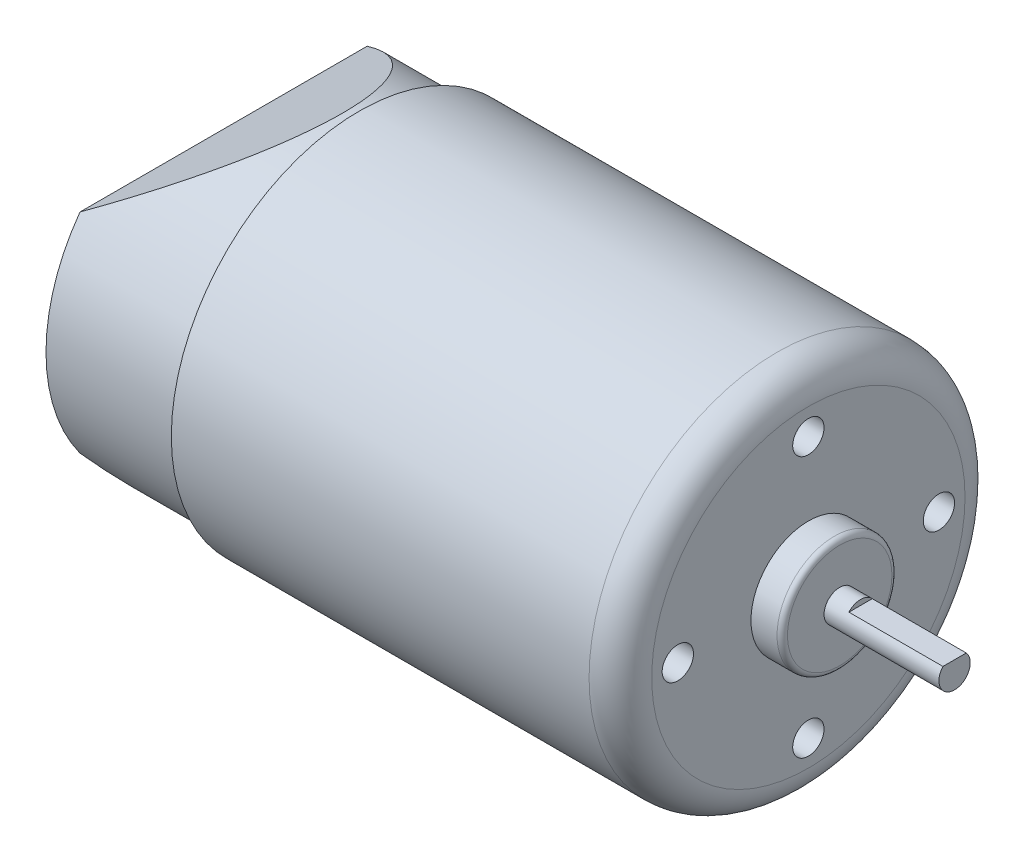
SolidWorks part; units mm, degrees
ref_plane "Front Plane" through (0, 0, 0) normal (0, 0, 1) x (1, 0, 0)
ref_plane "Top Plane" through (0, 0, 0) normal (0, 1, 0) x (1, 0, 0)
ref_plane "Right Plane" through (0, 0, 0) normal (1, 0, 0) x (0, 0, -1)
sketch "Sketch1" plane through (0, 0, 0) normal (1, 0, 0) x (0, 0, -1)
  circle A0 centre (0, 0) radius 18
  dimension "D1" = 36
extrude "Boss-Extrude1" add sketch "Sketch1" along normal blind 56
fillet "Fillet1" radius 3 1 edges at (56, 0, -18)
sketch "Sketch2" plane through (0, 0, 0) normal (0, 0, 1) x (1, 0, 0)
  line L0 (13, 18) -> (0, 10)
  line L1 (53, 18) -> (0, 18) construction
  line L2 (0, 18) -> (0, -18) construction
  line L3 (0, 10) -> (0, -10)
  line L4 (0, -10) -> (13, -18)
  line L5 (0, -18) -> (53, -18) construction
  line L6 (13, -18) -> (0, -18)
  line L7 (0, -18) -> (-7.8038, 17.2258)
  line L8 (-7.8038, 17.2258) -> (0, 18)
  line L9 (0, 18) -> (13, 18)
  dimension "D1" = 13
  dimension "D2" = 8
extrude "Cut-Extrude1" cut sketch "Sketch2" against normal up to surface and the other way up to surface
sketch "Sketch3" plane through (0, 0, 0) normal (0, 0, 1) x (1, 0, 0)
  line L0 (13, 18) -> (13, 17)
  line L1 (13, 17) -> (0, 17)
  line L2 (0, 17) -> (0, 18)
  line L3 (-7.8038, 17.2258) -> (0, 18) construction
  line L4 (0, 18) -> (13, 18)
  line L6 (0, 10) -> (0, -10) construction
  line L7 (-1000, 0) -> (49000, 0) construction
  dimension "D1" = 1
revolve "Cut-Revolve1" cut sketch "Sketch3" angle 360 about L7
sketch "Sketch4" plane through (56, 0, 0) normal (1, 0, 0) x (0, 0, -1)
  circle A0 centre (0, 0) radius 5.5
  dimension "D1" = 11
extrude "Boss-Extrude2" add sketch "Sketch4" along normal blind 3
fillet "Fillet2" radius 0.5 1 edges at (59, 0, -5.5)
sketch "Sketch5" plane through (59, 0, 0) normal (1, 0, 0) x (0, 0, -1)
  circle A0 centre (0, 0) radius 1.5
  dimension "D1" = 3
extrude "Boss-Extrude3" add sketch "Sketch5" along normal blind 11
sketch "Sketch6" plane through (0, 0, 0) normal (0, 0, 1) x (1, 0, 0)
  line L0 (70, 1.5) -> (70, 1)
  line L1 (70, -1.5) -> (70, 1.5) construction
  line L2 (70, 1) -> (61, 1)
  line L3 (61, 1) -> (61, 1.5)
  line L4 (70, 1.5) -> (59, 1.5) construction
  line L5 (61, 1.5) -> (70, 1.5)
  dimension "D1" = 9
  dimension "D2" = 0.5
extrude "Cut-Extrude2" cut sketch "Sketch6" against normal up to surface and the other way up to surface up to face at (70, 0, -1.5) other way up to face at (70, 0, -1.5)
sketch "Sketch7" plane through (56, 0, 0) normal (1, 0, 0) x (0, 0, -1)
  circle A0 centre (0, 12.5) radius 1.5
  circle A1 centre (0, 0) radius 5.5 construction
  circle A2 centre (12.5, 0) radius 1.5
  circle A3 centre (0, -12.5) radius 1.5
  circle A4 centre (-12.5, 0) radius 1.5
  dimension "D1" = 3
  dimension "D2" = 12.5
  dimension "D3" = 4
extrude "Cut-Extrude3" cut sketch "Sketch7" against normal blind 3
sketch "Sketch8" plane through (0, 0, 0) normal (0, 1, 0) x (1, 0, 0)
  line L0 (-1000, 0) -> (49000, 0) construction
  point P1 (-40, 0)
  dimension "D1" = 40
